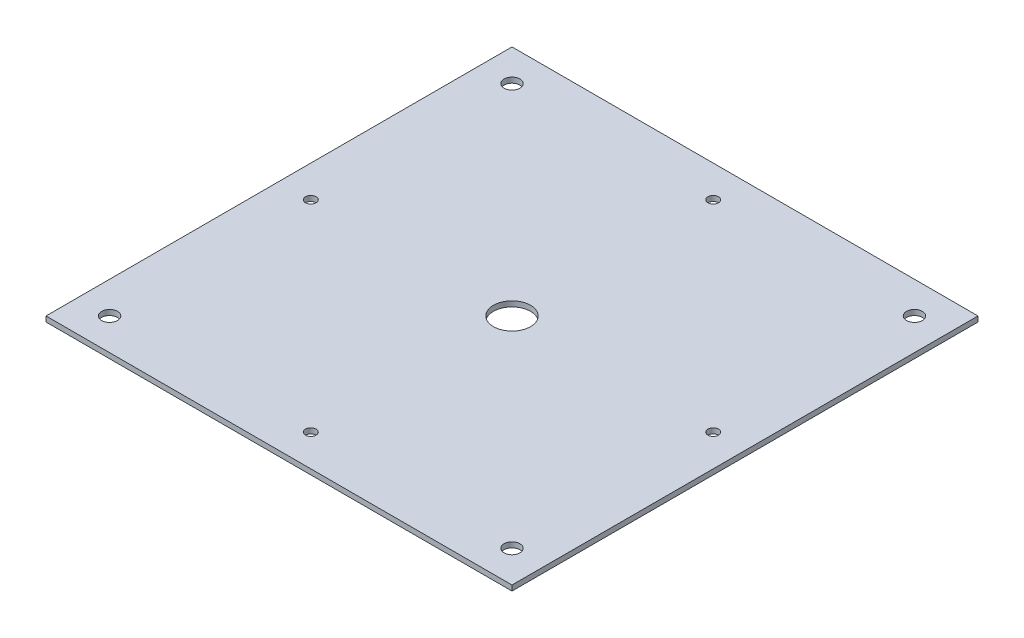
SolidWorks part; units mm, degrees
ref_plane "Front Plane" through (0, 0, 0) normal (0, 0, 1) x (1, 0, 0)
ref_plane "Top Plane" through (0, 0, 0) normal (0, 1, 0) x (1, 0, 0)
ref_plane "Right Plane" through (0, 0, 0) normal (1, 0, 0) x (0, 0, -1)
sketch "Sketch1" plane through (0, 0, 0) normal (0, 1, 0) x (1, 0, 0)
  line L1 (139.7, -139.7) -> (-139.7, -139.7)
  line L2 (139.7, -139.7) -> (139.7, 139.7)
  line L3 (139.7, 139.7) -> (-139.7, 139.7)
  line L4 (-139.7, -139.7) -> (-139.7, 139.7)
  line L5 (139.7, -139.7) -> (-139.7, 139.7) construction
  line L6 (139.7, 139.7) -> (-139.7, -139.7) construction
  circle A0 centre (0, 0) radius 11.1125
  point P0 (0, 0)
  point P6 (0, 0)
  dimension "D1" = 279.4
  dimension "D2" = 279.4
extrude "Boss-Extrude1" add sketch "Sketch1" along normal blind 3.175
sketch "Sketch2" plane through (0, 3.175, 0) normal (0, 1, 0) x (1, 0, 0)
  line L0 (0, -139.7) -> (0, 139.7) construction
  line L1 (-139.7, 0) -> (139.7, 0) construction
  line L2 (-139.7, -139.7) -> (139.7, -139.7) construction
  line L3 (139.7, 139.7) -> (-139.7, 139.7) construction
  line L4 (-139.7, 139.7) -> (-139.7, -139.7) construction
  line L5 (139.7, -139.7) -> (139.7, 139.7) construction
  circle A0 centre (0, 120.65) radius 3.175
  circle A1 centre (120.65, 0) radius 3.175
  circle A2 centre (0, -120.65) radius 3.175
  circle A3 centre (-120.65, 0) radius 3.175
  circle A5 centre (-120.65, 120.65) radius 4.7625
  circle A6 centre (120.65, 120.65) radius 4.7625
  circle A7 centre (-120.65, -120.65) radius 4.7625
  circle A8 centre (120.65, -120.65) radius 4.7625
  point P12 (0, 0)
  point P27 (0, 0)
  dimension "D3" = 6.35
  dimension "D1" = 120.65
  dimension "D2" = 4
extrude "Cut-Extrude1" cut sketch "Sketch2" against normal through all
